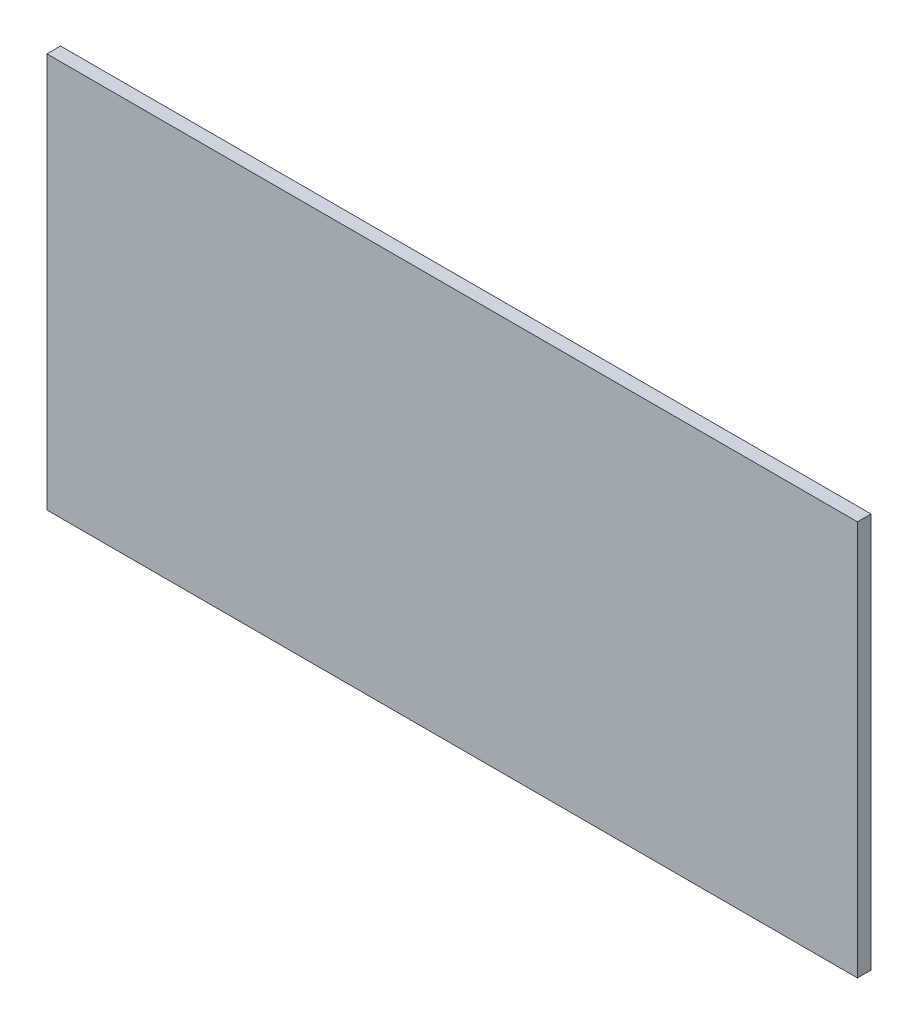
SolidWorks part; units mm, degrees
ref_plane "Спереди" through (0, 0, 0) normal (0, 0, 1) x (1, 0, 0)
ref_plane "Сверху" through (0, 0, 0) normal (0, 1, 0) x (1, 0, 0)
ref_plane "Справа" through (0, 0, 0) normal (1, 0, 0) x (0, 0, -1)
sketch "Эскиз1" plane through (0, 0, 0) normal (0, 0, 1) x (1, 0, 0)
  line L1 (-297.5, 145) -> (297.5, 145)
  line L2 (-297.5, 145) -> (-297.5, -145)
  line L3 (-297.5, -145) -> (297.5, -145)
  line L4 (297.5, 145) -> (297.5, -145)
  line L5 (-297.5, 145) -> (297.5, -145) construction
  line L6 (-297.5, -145) -> (297.5, 145) construction
  point P0 (0, 0)
  dimension "D1" = 290
  dimension "D2" = 595
extrude "Бобышка-Вытянуть1" add sketch "Эскиз1" along normal blind 10
